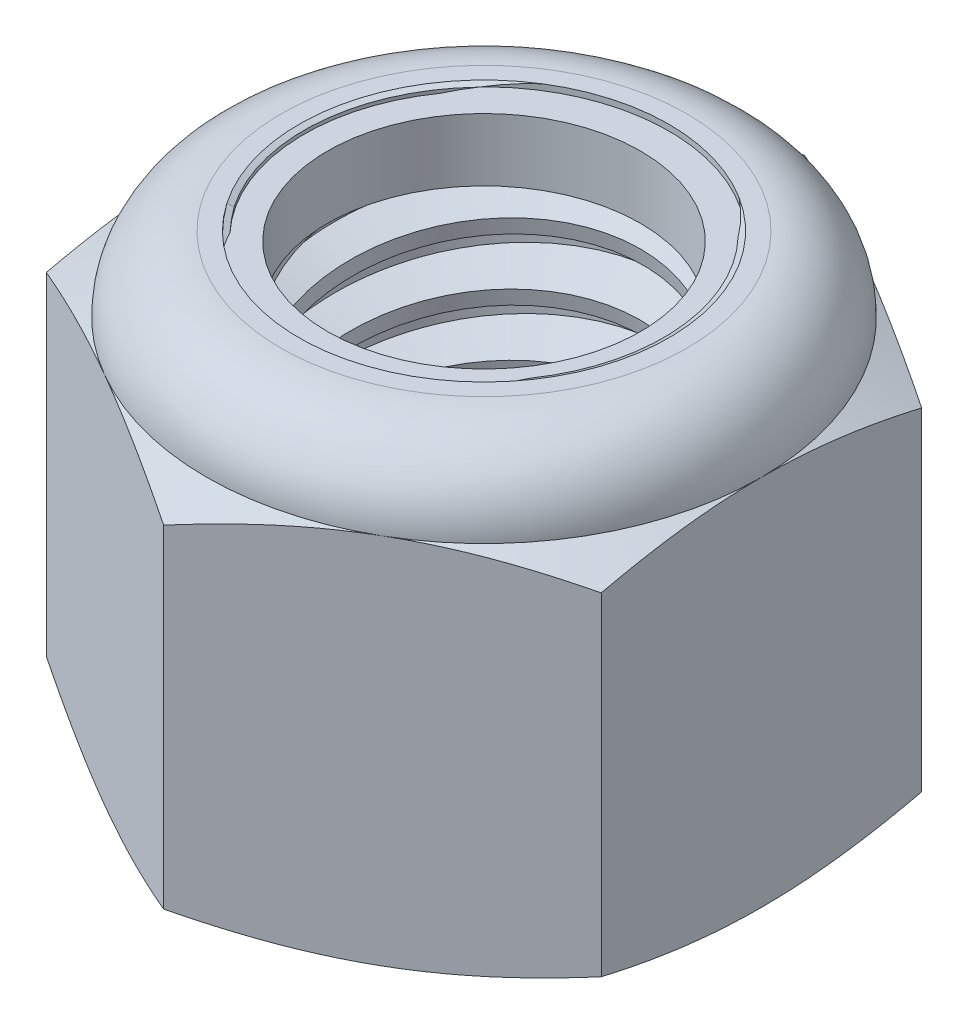
SolidWorks part; units mm, degrees
material "Alloy Steel"
ref_plane "Front" through (0, 0, 0) normal (0, 0, 1) x (1, 0, 0)
ref_plane "Top" through (0, 0, 0) normal (0, 1, 0) x (1, 0, 0)
ref_plane "Right" through (0, 0, 0) normal (1, 0, 0) x (0, 0, -1)
sketch "Sketch1" plane through (0, 0, 0) normal (0, 1, 0) x (1, 0, 0)
  line L1 (0, 8.2489) -> (-7.1438, 4.1244)
  line L2 (-7.1438, 4.1244) -> (-7.1438, -4.1244)
  line L3 (-7.1438, -4.1244) -> (0, -8.2489)
  line L4 (0, -8.2489) -> (7.1437, -4.1244)
  line L5 (7.1437, -4.1244) -> (7.1437, 4.1244)
  line L6 (7.1437, 4.1244) -> (0, 8.2489)
  circle A0 centre (0, 0) radius 7.1438 construction
  dimension "Hex Flats" = 14.2875
extrude "Extrude1" add sketch "Sketch1" along normal blind 11.5094
sketch "Sketch2" plane through (0, 0, 0) normal (1, 0, 0) x (0, 0, -1)
  line L0 (-4.7625, 0) -> (-4.7625, 11.5094) construction
  line L1 (0, 0) -> (4.7625, 0)
  line L2 (0, 0) -> (0, 11.5094)
  line L3 (0, 11.5094) -> (4.7625, 11.5094)
  line L4 (4.7625, 0) -> (4.7625, 11.5094)
  line L5 (-4.1244, 11.5094) -> (4.1244, 11.5094) construction
  line L7 (0, -4.7625) -> (0, 0) construction
  dimension "Thread Dia" = 9.525
revolve "Revolve1" add sketch "Sketch2" angle 360 about L7
sketch "Sketch3" plane through (0, 0, 0) normal (1, 0, 0) x (0, 0, -1)
  line L0 (4.7625, 11.5094) -> (-4.7625, 11.5094) construction
  line L1 (-4.7625, 11.5094) -> (-4.7625, 9.9219) construction
  line L2 (-4.7625, 9.9219) -> (4.7625, 11.5094) construction
  line L3 (4.7625, 11.5094) -> (4.7951, 11.3136) construction
  line L4 (4.7951, 11.3136) -> (5.0235, 9.9435)
  line L5 (5.0235, 9.9435) -> (4.0944, 10.2916)
  line L6 (4.0944, 10.2916) -> (4.0291, 10.683)
  line L7 (4.0291, 10.683) -> (4.7951, 11.3136)
  line L8 (4.0617, 10.4873) -> (4.9093, 10.6286) construction
  line L9 (4.7625, 11.5094) -> (4.7625, 10.6041) construction
  line L10 (4.7625, 10.6041) -> (-4.7625, 9.0166) construction
  line L11 (-4.7625, 9.0166) -> (-4.7625, 9.9219) construction
  line L12 (-0.2832, 11.5094) -> (0.2832, 8.1113) construction
  line L13 (-4.7625, 0) -> (-4.7625, 11.5094) construction
  line L14 (0, 11.5094) -> (4.7625, 11.5094) construction
  line L15 (4.7625, 0) -> (4.7625, 11.5094) construction
  point P13 (0, 9.8103)
  dimension "D1" = 0.1984
  dimension "D2" = 0.3969
  dimension "Thread Pitch" = 1.5875
  dimension "D4" = 60
  dimension "D5" = 1.5875
revolve "Cut-Revolve1" cut sketch "Sketch3" angle 360 about L12
pattern_linear "LPattern1" count 7 spacing 1.5875 along (0, -1, 0) count 2 spacing 1.5875 along (0, 1, 0) of "Cut-Revolve1"
sketch "Sketch4" plane through (0, 0, 0) normal (1, 0, 0) x (0, 0, -1)
  line L0 (0, 11.5094) -> (4.7625, 11.5094)
  line L1 (4.7625, 11.5094) -> (4.0291, 11.1674)
  line L2 (4.0291, 11.1674) -> (4.0291, 0.342)
  line L3 (4.0291, 0.342) -> (4.7625, 0)
  line L4 (4.7625, 0) -> (0, 0)
  line L5 (0, 0) -> (0, 11.5094)
  line L6 (4.7625, 0) -> (4.7625, 11.5094) construction
  line L7 (0, 11.5094) -> (4.7625, 11.5094) construction
  line L8 (0, 0) -> (4.7625, 0) construction
  line L9 (0, 0) -> (0, 11.5094) construction
  line L10 (0, 11.5094) -> (0, 12.3186) construction
  dimension "D1" = 25
revolve "Cut-Revolve2" cut sketch "Sketch4" angle 360 about L10
combine bodies "Combine1" operation type subtract main body 112 bodies to subtract 111
sketch "Sketch5" plane through (0, 0, 0) normal (1, 0, 0) x (0, 0, -1)
  line L0 (0, 0) -> (7.1438, 0)
  line L1 (7.1438, 0) -> (8.2489, 0.5153)
  line L2 (8.2489, 0.5153) -> (8.2489, 9.0758)
  line L3 (8.2489, 9.0758) -> (7.1438, 9.5911)
  line L4 (5.2255, 11.5094) -> (5.2255, 12.7794)
  line L5 (5.2255, 12.7794) -> (9.5189, 12.7794)
  line L6 (9.5189, 12.7794) -> (9.5189, -1.27)
  line L7 (9.5189, -1.27) -> (0, -1.27)
  line L8 (0, -1.27) -> (0, 0)
  line L9 (7.1438, 9.5911) -> (7.1438, 0) construction
  line L10 (0, 0) -> (4.7625, 0) construction
  line L13 (8.2489, 4.7956) -> (9.5189, 4.7956) construction
  line L14 (8.2489, 11.5094) -> (8.2489, 0) construction
  line L15 (0, 0) -> (0, 12.7794) construction
  line L20 (0, 12.7794) -> (5.2255, 12.7794) construction
  line L22 (0, 11.5094) -> (4.7625, 11.5094) construction
  arc A0 (7.1438, 9.5911) -> (5.2255, 11.5094) centre (5.2255, 9.5911) ccw
  dimension "D1" = 25
  dimension "D2" = 1.27
  dimension "D3" = 11.5094
  dimension "D4" = 1.9182
revolve "Cut-Revolve3" cut sketch "Sketch5" angle 360 about L15
sketch "Sketch6" plane through (0, 0, 0) normal (1, 0, 0) x (0, 0, -1)
  line L0 (0, 9.5911) -> (6.9914, 9.5911)
  line L1 (5.2255, 11.357) -> (4.6273, 11.357)
  line L2 (0, 12.7794) -> (0, 9.5911)
  line L3 (4.6273, 12.7794) -> (0, 12.7794)
  line L4 (0, 12.7794) -> (5.2255, 12.7794) construction
  line L5 (0, 0) -> (0, 12.7794) construction
  line L6 (0, 12.7794) -> (0, 44.323) construction
  line L7 (4.6273, 11.357) -> (4.6273, 12.7794)
  line L8 (5.2255, 11.5094) -> (5.2255, 11.357) construction
  line L9 (4.6273, 11.357) -> (4.0291, 11.357) construction
  line L10 (4.0291, 11.357) -> (4.0291, 11.1674) construction
  arc A0 (6.9914, 9.5911) -> (5.2255, 11.357) centre (5.2255, 9.5911) ccw
  arc A1 (7.1438, 9.5911) -> (5.2255, 11.5094) centre (5.2255, 9.5911) ccw construction
  dimension "D1" = 0.1524
revolve "Cut-Revolve4" cut sketch "Sketch6" angle 360 about L6
sketch "Sketch7" plane through (0, 0, 0) normal (1, 0, 0) x (0, 0, -1)
  line L0 (4.0291, 9.6673) -> (6.9134, 9.6673)
  line L1 (5.2255, 11.2808) -> (4.0291, 11.2808)
  line L2 (4.0291, 11.2808) -> (4.0291, 9.6673)
  line L3 (4.0291, 9.6673) -> (0, 9.6673) construction
  line L4 (0, 9.6673) -> (0, 11.2808) construction
  line L5 (0, 11.2808) -> (4.0291, 11.2808) construction
  line L6 (4.0291, 9.6673) -> (4.0291, 9.5911) construction
  line L7 (0, 9.5911) -> (6.9914, 9.5911) construction
  line L8 (5.2255, 11.2808) -> (5.2255, 11.357) construction
  arc A0 (6.9134, 9.6673) -> (5.2255, 11.2808) centre (5.2255, 9.5911) ccw
  arc A2 (6.9914, 9.5911) -> (5.2255, 11.357) centre (5.2255, 9.5911) ccw construction
  dimension "D1" = 0.0762
revolve "Revolve2" add sketch "Sketch7" angle 360 about L4
equation "\"D1@Sketch3\"=\"Thread Pitch@Sketch3\"/8"
equation "\"D2@Sketch3\"=\"Thread Pitch@Sketch3\"/4"
equation "\"D5@Sketch3\"=\"Thread Pitch@Sketch3\""
equation "\"D4@LPattern1\"=\"Thread Pitch@Sketch3\""
equation "\"D3@LPattern1\"=\"Thread Pitch@Sketch3\""
equation "\"D1@LPattern1\"=\"Height@Extrude1\"/\"Thread Pitch@Sketch3\""
equation "\"D4@Sketch5\"=\"Height@Extrude1\"/6"
